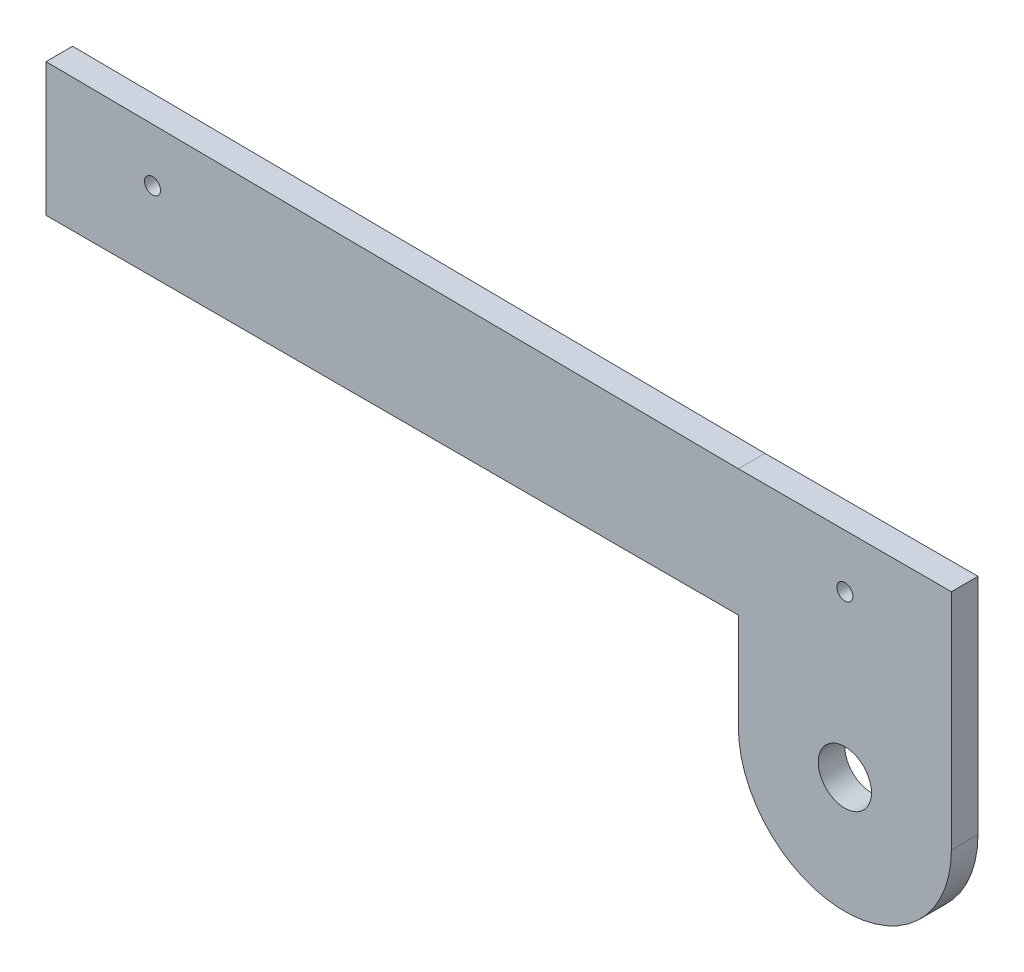
SolidWorks part; units mm, degrees
ref_plane "Front Plane" through (0, 0, 0) normal (0, 0, 1) x (1, 0, 0)
ref_plane "Top Plane" through (0, 0, 0) normal (0, 1, 0) x (1, 0, 0)
ref_plane "Right Plane" through (0, 0, 0) normal (1, 0, 0) x (0, 0, -1)
sketch "Sketch1" plane through (0, 0, 0) normal (0, 0, 1) x (1, 0, 0)
  line L0 (0, 78.0535) -> (0, -76.7078) construction
  line L1 (-108.1983, 0.6729) -> (119.7718, 0.6729) construction
  line L2 (-12.0732, -76.7078) -> (17.2347, -76.7078) construction
  line L3 (-20, -76.7078) -> (-20, -58.5041)
  line L4 (-20, -34.7078) -> (20, -34.7078)
  line L5 (20, -34.7078) -> (20, -76.7078)
  line L6 (-20, -34.7078) -> (-150, -33.5041)
  line L7 (-150, -33.5041) -> (-150, -58.5041)
  line L8 (-150, -58.5041) -> (-20, -58.5041)
  arc A0 (-20, -76.7078) -> (20, -76.7078) centre (0, -76.7078) ccw
  circle A1 centre (0, -44.7078) radius 1.5
  circle A2 centre (-130, -43.6897) radius 1.5
  dimension "D1" = 40
  dimension "D10" = 3
  dimension "D11" = 3
  dimension "D2" = 40
  dimension "D3" = 42
  dimension "D4" = 130
  dimension "D5" = 25
  dimension "D6" = 130
  dimension "D7" = 10
  dimension "D8" = 10
  dimension "D9" = 20
extrude "Boss-Extrude1" add sketch "Sketch1" along normal blind 5
sketch "Sketch2" plane through (0, 0, 5) normal (0, 0, 1) x (1, 0, 0)
  line L0 (0, -39.6329) -> (0, -110.1829) construction
  line L1 (-29.4048, -74.9079) -> (47.7155, -74.9079) construction
  circle A0 centre (0, -74.9079) radius 5
extrude "Cut-Extrude1" cut sketch "Sketch2" against normal blind 24 and the other way blind 37
